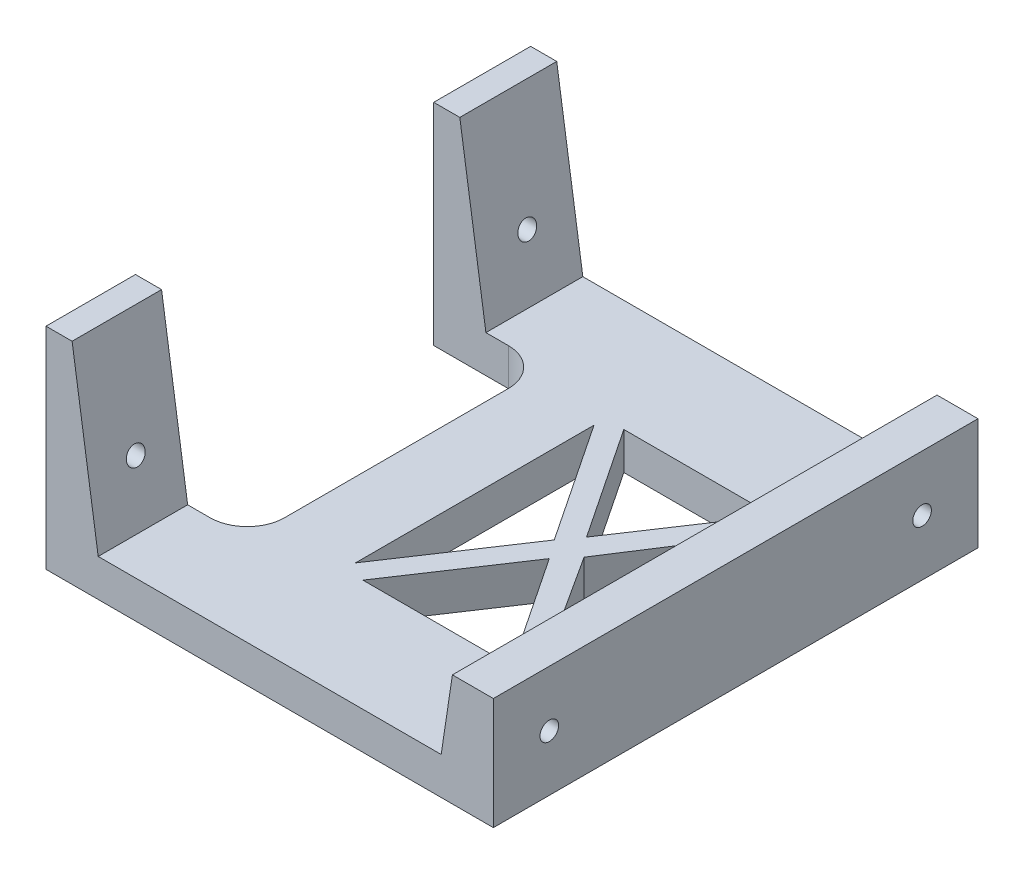
SolidWorks part; units mm, degrees
material "1060 Alloy"
ref_plane "Front Plane" through (0, 0, 0) normal (0, 0, 1) x (1, 0, 0)
ref_plane "Top Plane" through (0, 0, 0) normal (0, 1, 0) x (1, 0, 0)
ref_plane "Right Plane" through (0, 0, 0) normal (1, 0, 0) x (0, 0, -1)
sketch "Sketch1" plane through (0, 0, 0) normal (0, 0, 1) x (1, 0, 0)
  line L0 (-20.9345, 0) -> (55.2655, 0)
  line L1 (55.2655, 0) -> (55.2655, 35.8775)
  line L2 (55.2655, 35.8775) -> (50.8205, 35.8775)
  line L3 (50.8205, 35.8775) -> (46.3755, 6.35)
  line L4 (46.3755, 6.35) -> (-12.0445, 6.35)
  line L5 (-12.0445, 6.35) -> (-16.4895, 35.8775)
  line L6 (-16.4895, 35.8775) -> (-20.9345, 35.8775)
  line L7 (-20.9345, 35.8775) -> (-20.9345, 0)
  dimension "D1" = 8.89
  dimension "D2" = 8.89
  dimension "D3" = 4.445
  dimension "D4" = 4.445
  dimension "D5" = 76.2
  dimension "D6" = 35.8775
  dimension "D7" = 6.35
extrude "Boss-Extrude1" add sketch "Sketch1" along normal blind 82.55
sketch "Sketch2" plane through (0, 35.8775, 0) normal (0, 1, 0) x (1, 0, 0)
  line L0 (-1.8845, -53.975) -> (-1.8845, -28.575)
  line L1 (46.3755, 0) -> (-12.0445, 0) construction
  line L2 (-20.9345, -82.55) -> (-20.9345, 0) construction
  line L3 (-20.9345, -16.51) -> (-20.9345, -67.31)
  line L4 (-20.9345, -16.51) -> (-1.8845, -16.51)
  line L5 (-1.8845, -16.51) -> (-1.8845, -28.575)
  line L6 (-1.8845, -53.975) -> (-1.8845, -67.31)
  line L7 (-1.8845, -67.31) -> (-20.9345, -67.31)
  line L8 (-16.4895, 0) -> (-20.9345, 0) construction
  point P12 (-18.712, 0)
  dimension "D1" = 25.4
  dimension "D2" = 28.575
  dimension "D3" = 19.05
  dimension "D4" = 50.8
  dimension "D5" = 16.51
extrude "Cut-Extrude1" cut sketch "Sketch2" against normal blind 50.8
fillet "Fillet1" radius 6.35 2 edges at (-1.8845, 3.175, 16.51) (-1.8845, 3.175, 67.31)
sketch "Sketch3" plane through (0, 0, 82.55) normal (0, 0, 1) x (1, 0, 0)
  line L1 (42.6345, 40.9078) -> (61.4512, 40.9078)
  line L2 (42.6345, 40.9078) -> (42.6345, 19.05)
  line L3 (42.6345, 19.05) -> (61.4512, 19.05)
  line L4 (61.4512, 40.9078) -> (61.4512, 19.05)
  line L5 (-20.9345, 0) -> (55.2655, 0) construction
  dimension "D1" = 19.05
extrude "Cut-Extrude2" cut sketch "Sketch3" against normal blind 101.6
sketch "Sketch4" plane through (0, 0, 0) normal (0, -1, 0) x (1, 0, 0)
  line L0 (13.9905, 63.5) -> (39.3905, 63.5)
  line L1 (39.3905, 63.5) -> (26.6905, 44.45)
  line L2 (26.6905, 44.45) -> (13.9905, 63.5)
  line L3 (10.8155, 61.595) -> (24.3622, 41.275)
  line L4 (24.3622, 41.275) -> (10.8155, 20.955)
  line L5 (10.8155, 20.955) -> (10.8155, 61.595)
  line L6 (42.5655, 61.595) -> (42.5655, 20.955)
  line L7 (42.5655, 20.955) -> (29.4422, 41.275)
  line L8 (29.4422, 41.275) -> (42.5655, 61.595)
  line L9 (13.9905, 19.05) -> (26.6905, 38.1)
  line L10 (26.6905, 38.1) -> (39.3905, 19.05)
  line L11 (39.3905, 19.05) -> (13.9905, 19.05)
  line L12 (-20.9345, 0) -> (55.2655, 0) construction
  line L13 (-20.9345, 82.55) -> (55.2655, 82.55) construction
  line L14 (55.2655, 82.55) -> (55.2655, 0) construction
  line L15 (-1.8845, 60.96) -> (-1.8845, 22.86) construction
  line L16 (-8.2345, 16.51) -> (-20.9345, 16.51) construction
  dimension "D1" = 19.05
  dimension "D2" = 19.05
  dimension "D3" = 12.7
  dimension "D4" = 12.7
  dimension "D5" = 40.64
  dimension "D6" = 25.4
  dimension "D7" = 15.875
  dimension "D8" = 6.35
  dimension "D9" = 4.445
  dimension "D10" = 5.08
extrude "Cut-Extrude3" cut sketch "Sketch4" against normal blind 50.8
sketch "Sketch5" plane through (-20.9345, 0, 0) normal (-1, 0, 0) x (0, 0, 1)
  line L0 (16.51, 0) -> (0, 0) construction
  line L1 (0, 35.8775) -> (0, 0) construction
  line L2 (82.55, 35.8775) -> (82.55, 0) construction
  circle A0 centre (7.9375, 16.51) radius 1.5875
  circle A1 centre (74.6125, 16.51) radius 1.5875
  dimension "D1" = 3.175
  dimension "D2" = 16.51
  dimension "D3" = 7.9375
  dimension "D4" = 7.9375
extrude "Cut-Extrude4" cut sketch "Sketch5" against normal blind 25.4
sketch "Sketch6" plane through (55.2655, 0, 0) normal (1, 0, 0) x (0, 0, -1)
  line L0 (-82.55, 0) -> (0, 0) construction
  line L1 (-82.55, 0) -> (-82.55, 19.05) construction
  line L2 (0, 0) -> (0, 19.05) construction
  circle A0 centre (-9.525, 9.525) radius 1.5875
  circle A1 centre (-73.025, 9.525) radius 1.5875
  point P4 (0, 0)
  point P7 (0, 0)
  point P9 (-57.6446, -15.1607)
  dimension "D4" = 3.175
  dimension "D5" = 3.175
  dimension "D1" = 9.525
  dimension "D2" = 9.525
  dimension "D3" = 9.525
extrude "Cut-Extrude5" cut sketch "Sketch6" against normal blind 10.16
